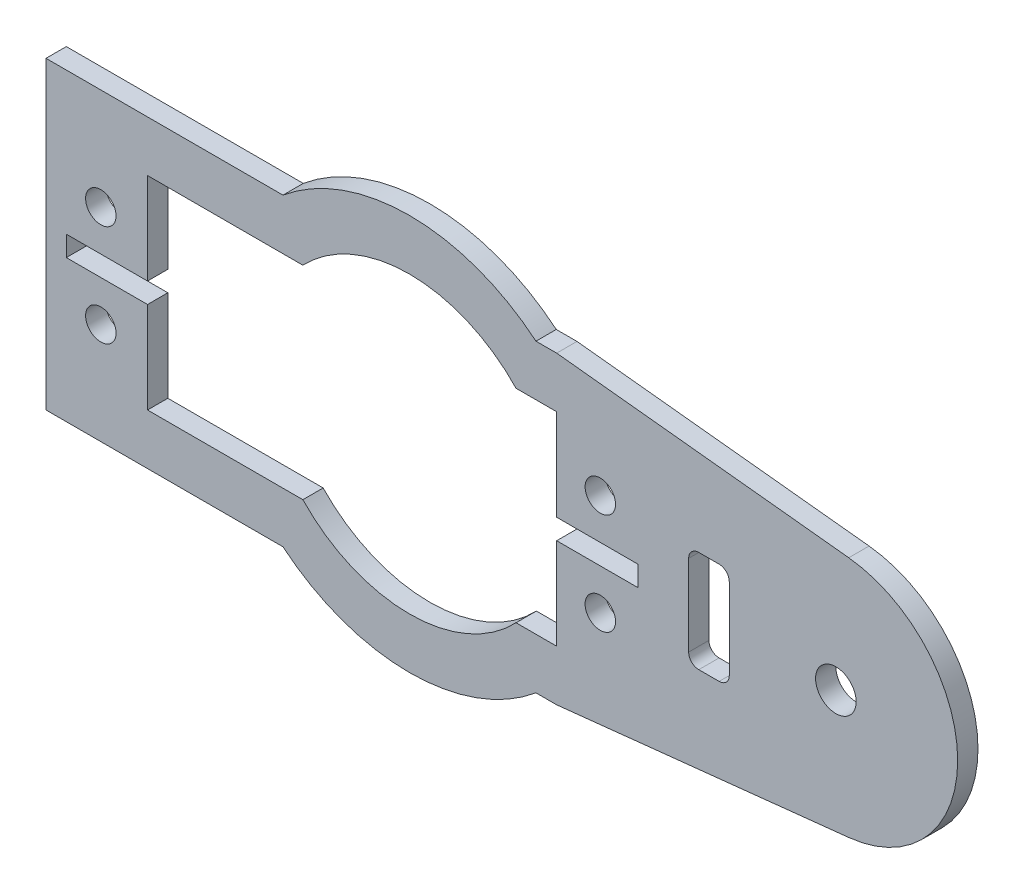
SolidWorks part; units mm, degrees
ref_plane "Спереди" through (0, 0, 0) normal (0, 0, 1) x (1, 0, 0)
ref_plane "Сверху" through (0, 0, 0) normal (0, 1, 0) x (1, 0, 0)
ref_plane "Справа" through (0, 0, 0) normal (1, 0, 0) x (0, 0, -1)
sketch "Sketch1" plane through (0, 0, 0) normal (0, 0, 1) x (1, 0, 0)
  line L0 (1.2722, -11.9324) -> (-27.5, -15)
  line L1 (1.2722, 11.9324) -> (-27.5, 15)
  line L2 (-27.5, 15) -> (-29.5401, 15)
  line L3 (-27.5, -15) -> (-29.5401, -15)
  line L4 (-77.8, 15) -> (-77.8, -15)
  line L5 (112.1325, 0) -> (-112.1325, 0) construction
  line L6 (-54.4599, -15) -> (-77.8, -15)
  line L7 (-54.4599, 15) -> (-77.8, 15)
  circle A0 centre (0, 0) radius 2
  arc A1 (1.2722, 11.9324) -> (1.2722, -11.9324) centre (0, 0) cw
  arc A2 (-54.4599, -15) -> (-29.5401, -15) centre (-42, 0) ccw
  arc A3 (-29.5401, 15) -> (-54.4599, 15) centre (-42, 0) ccw
  point P2 (-77.8, 0)
  point P12 (0, 0)
  dimension "D1" = 4
  dimension "D2" = 12
  dimension "D7" = 39
  dimension "D8" = 42
  dimension "D3" = 50.3
  dimension "D4" = 50.3
  dimension "D5" = 30
  dimension "D6" = 77.8
  dimension "D9" = 15
extrude "Extrude1" add sketch "Sketch1" along normal blind 2
sketch "Sketch2" plane through (0, 0, 2) normal (0, 0, 1) x (1, 0, 0)
  line L0 (0, 0) -> (-41.6657, 0) construction
  circle A0 centre (-23.2, 5) radius 1.5
  circle A3 centre (-72.4, 5) radius 1.5
  circle A4 centre (-23.2, -5) radius 1.5
  circle A5 centre (0, 0) radius 2 construction
  circle A6 centre (-72.4, -5) radius 1.5
  dimension "D1" = 23.2
  dimension "D2" = 5
  dimension "D3" = 3
  dimension "D4" = 3
  dimension "D5" = 5
  dimension "D6" = 72.4
extrude "Extrude2" cut sketch "Sketch2" against normal blind 2
sketch "Sketch3" plane through (0, 0, 2) normal (0, 0, 1) x (1, 0, 0)
  line L1 (-13.5, 5) -> (-11.5, 5)
  line L2 (-14.5, 4) -> (-14.5, -4)
  line L3 (-13.5, -5) -> (-11.5, -5)
  line L4 (-10.5, 4) -> (-10.5, -4)
  arc A1 (-14.5, -4) -> (-13.5, -5) centre (-13.5, -4) ccw
  arc A2 (-11.5, -5) -> (-10.5, -4) centre (-11.5, -4) ccw
  arc A3 (-11.5, 5) -> (-10.5, 4) centre (-11.5, 4) cw
  arc A4 (-13.5, 5) -> (-14.5, 4) centre (-13.5, 4) ccw
  point P6 (-12.5, 5)
  point P10 (-14.5, -5)
  point P17 (-14.5, 5)
  dimension "D5" = 1
  dimension "D1" = 10.5
  dimension "D2" = 4
  dimension "D3" = 10
  dimension "D4" = 5
extrude "Extrude3" cut sketch "Sketch3" against normal blind 2
sketch "Sketch4" plane through (0, 0, 2) normal (0, 0, 1) x (1, 0, 0)
  line L0 (-27.5, -1) -> (-27.5, -10)
  line L1 (-27.5, 1) -> (-19.5, 1)
  line L3 (-27.5, -1) -> (-19.5, -1)
  line L4 (-19.5, 1) -> (-19.5, -1)
  line L9 (-67.8, 10) -> (-27.5, 10)
  line L11 (-67.8, -10) -> (-27.5, -10)
  line L12 (-27.5, 10) -> (-27.5, 1)
  line L13 (0, 0) -> (-54.4804, 0) construction
  line L14 (-47.65, 10) -> (-47.65, -10) construction
  line L15 (-67.8, -1) -> (-67.8, -10)
  line L16 (-67.8, -1) -> (-75.8, -1)
  line L17 (-75.8, 1) -> (-75.8, -1)
  line L18 (-67.8, 1) -> (-75.8, 1)
  line L19 (-67.8, 10) -> (-67.8, 1)
  circle A0 centre (0, 0) radius 2 construction
  point P12 (-23.5, -1)
  dimension "D1" = 19.5
  dimension "D2" = 8
  dimension "D3" = 9
  dimension "D4" = 2
  dimension "D5" = 9
  dimension "D6" = 1
  dimension "D7" = 20.15
extrude "Extrude4" cut sketch "Sketch4" against normal blind 2
sketch "Sketch5" plane through (0, 0, 2) normal (0, 0, 1) x (1, 0, 0)
  line L0 (-27.5, 10) -> (-27.5, -10) construction
  line L1 (-67.8, -10) -> (-27.5, -10) construction
  circle A0 centre (-42, 0) radius 14.5
  point P4 (-27.5, 0)
  dimension "D1" = 29
  dimension "D2" = 42
  dimension "D3" = 10
extrude "Extrude5" cut sketch "Sketch5" against normal blind 2
